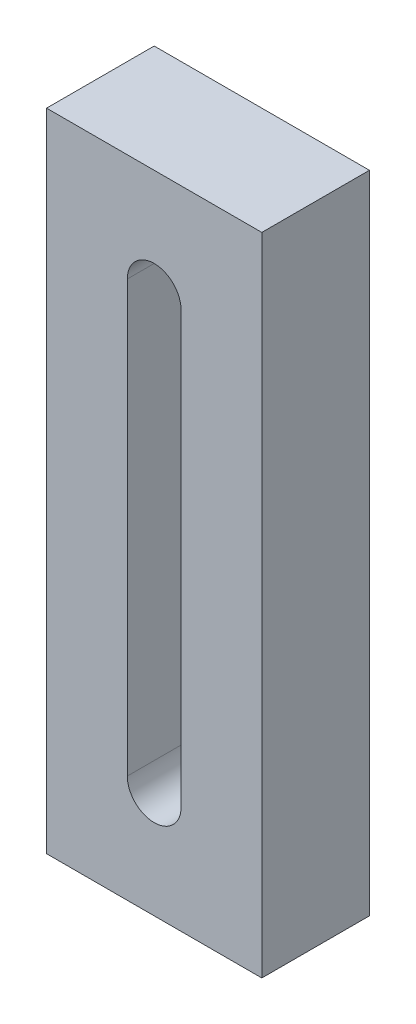
SolidWorks part; units mm, degrees
ref_plane "Front Plane" through (0, 0, 0) normal (0, 0, 1) x (1, 0, 0)
ref_plane "Top Plane" through (0, 0, 0) normal (0, 1, 0) x (1, 0, 0)
ref_plane "Right Plane" through (0, 0, 0) normal (1, 0, 0) x (0, 0, -1)
sketch "Sketch1" plane through (0, 0, 0) normal (0, 0, 1) x (1, 0, 0)
  line L0 (0, 76.2) -> (0, -76.2)
  line L1 (0, -76.2) -> (50.8, -76.2)
  line L2 (50.8, -76.2) -> (50.8, 76.2)
  line L3 (50.8, 76.2) -> (0, 76.2)
  point P5 (50.8, 70.536)
  point P6 (0, 0)
  dimension "D1" = 152.4
  dimension "D2" = 50.8
extrude "Boss-Extrude1" add sketch "Sketch1" along normal blind 25.4 contours L3 L0 L1 L2
sketch "Sketch2" plane through (0, 0, 25.4) normal (0, 0, 1) x (1, 0, 0)
  line L0 (25.4, 50.8) -> (25.4, -50.8) construction
  line L1 (31.75, 50.8) -> (31.75, -50.8)
  line L2 (19.05, 50.8) -> (19.05, -50.8)
  line L4 (50.8, 76.2) -> (0, 76.2) construction
  arc A0 (31.75, 50.8) -> (19.05, 50.8) centre (25.4, 50.8) ccw
  arc A1 (19.05, -50.8) -> (31.75, -50.8) centre (25.4, -50.8) ccw
  point P2 (25.4, 0)
  point P7 (0, 0)
  point P10 (25.4, 76.2)
  dimension "D1" = 101.6
  dimension "D2" = 12.7
extrude "Cut-Extrude1" cut sketch "Sketch2" against normal through all both and the other way through all contours L2 A1 L1 A0
